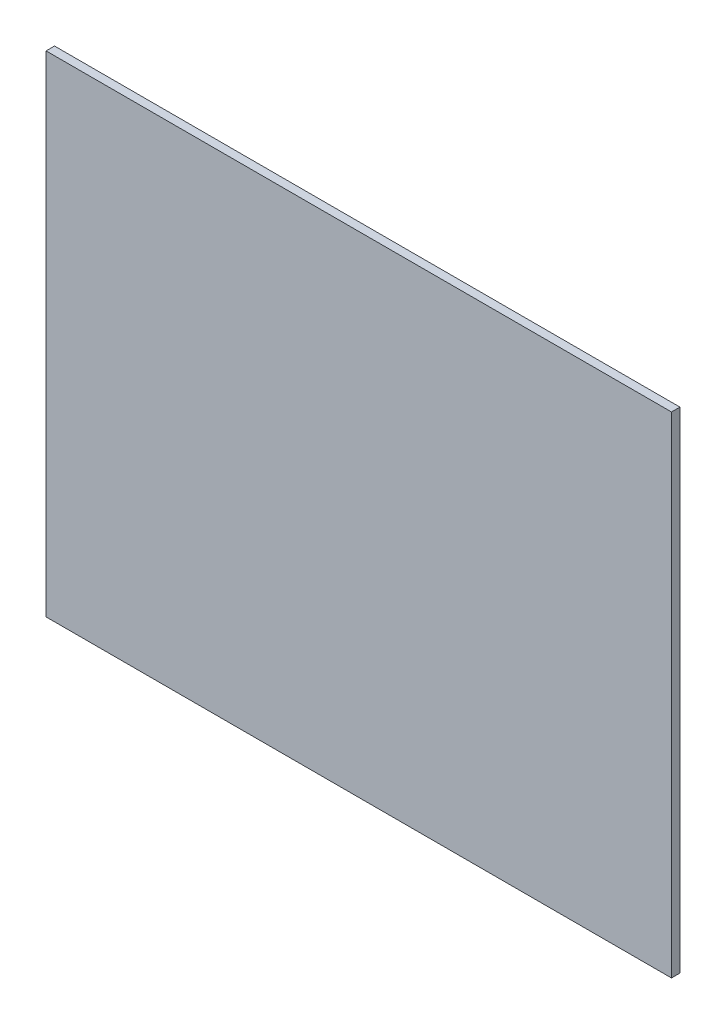
SolidWorks part; units mm, degrees
ref_plane "Front Plane" through (0, 0, 0) normal (0, 0, 1) x (1, 0, 0)
ref_plane "Top Plane" through (0, 0, 0) normal (0, 1, 0) x (1, 0, 0)
ref_plane "Right Plane" through (0, 0, 0) normal (1, 0, 0) x (0, 0, -1)
sketch "Sketch1" plane through (0, 0, 0) normal (0, 0, 1) x (1, 0, 0)
  line L4 (-1.72, 0.87) -> (-1.72, -0.87)
  line L5 (-1.72, -0.87) -> (0.5, -0.87)
  line L6 (-1.72, 0.87) -> (-1.72, -0.87)
  line L7 (0.5, 0.87) -> (-1.72, 0.87)
  line L9 (-1.72, -0.87) -> (0.5, -0.87)
  line L11 (0.5, 0.87) -> (-1.72, 0.87)
  line L16 (0.5, -0.87) -> (0.5, 0.87)
  line L17 (0.5, -0.87) -> (0.5, 0.87)
  dimension "D1" = 0
extrude "Boss-Extrude1" add sketch "Sketch1" against normal up to surface (0.03 mm away)
